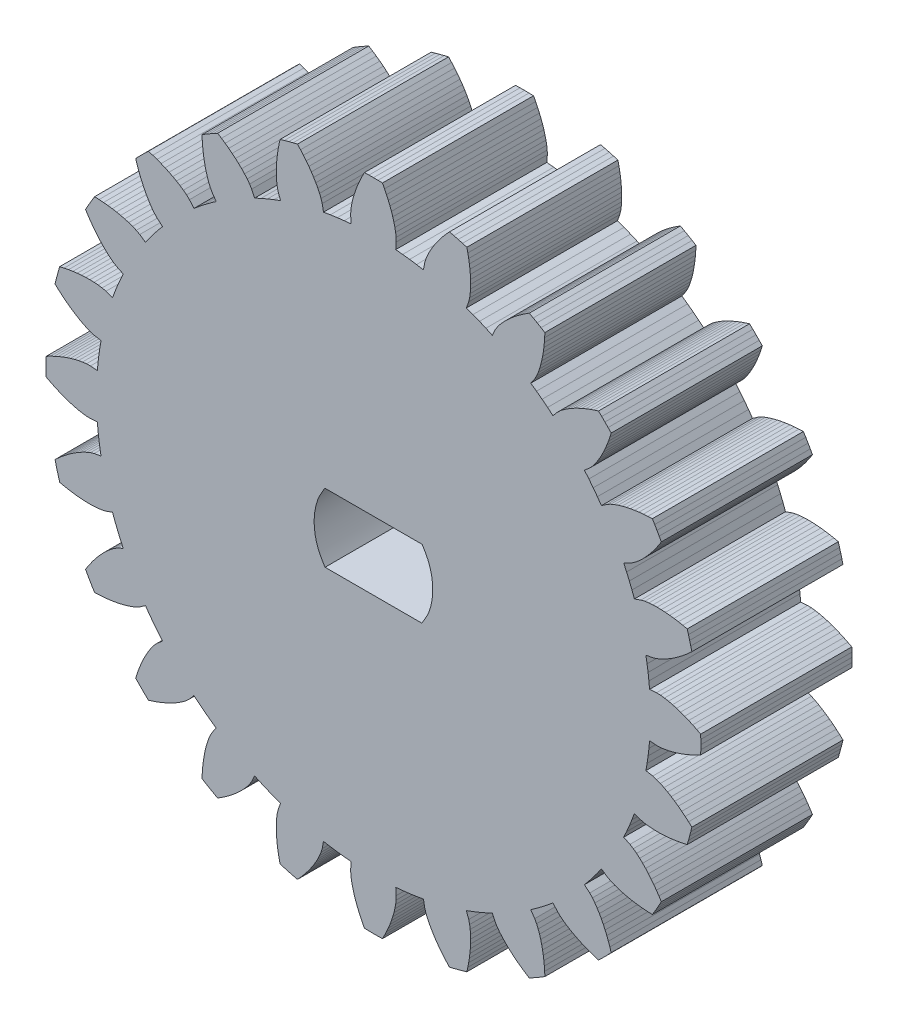
SolidWorks part; units mm, degrees
ref_plane "Front Plane" through (0, 0, 0) normal (0, 0, 1) x (1, 0, 0)
ref_plane "Top Plane" through (0, 0, 0) normal (0, 1, 0) x (1, 0, 0)
ref_plane "Right Plane" through (0, 0, 0) normal (1, 0, 0) x (0, 0, -1)
sketch "Model" plane through (0, 0, 0) normal (0, 0, 1) x (1, 0, 0)
  line L0 (117.0733, 147.6607) -> (117.2309, 147.6558)
  line L1 (117.2309, 147.6558) -> (117.3895, 147.636)
  line L2 (117.3895, 147.636) -> (117.5489, 147.6061)
  line L3 (117.5489, 147.6061) -> (117.7087, 147.5679)
  line L4 (117.7087, 147.5679) -> (117.8688, 147.5221)
  line L5 (117.8688, 147.5221) -> (118.029, 147.4694)
  line L6 (118.029, 147.4694) -> (118.1892, 147.4101)
  line L7 (118.1892, 147.4101) -> (118.3494, 147.3447)
  line L8 (118.3494, 147.3447) -> (118.5094, 147.2733)
  line L9 (118.5094, 147.2733) -> (118.6691, 147.1961)
  line L10 (118.6691, 147.1961) -> (118.8284, 147.1133)
  line L11 (118.8284, 147.1133) -> (118.8321, 146.9344)
  line L12 (118.8321, 146.9344) -> (118.8332, 146.7556)
  line L13 (118.8332, 146.7556) -> (118.8321, 146.5767)
  line L14 (118.8321, 146.5767) -> (118.8284, 146.3978)
  line L15 (118.8284, 146.3978) -> (118.6691, 146.315)
  line L16 (118.6691, 146.315) -> (118.5094, 146.2378)
  line L17 (118.5094, 146.2378) -> (118.3494, 146.1664)
  line L18 (118.3494, 146.1664) -> (118.1892, 146.101)
  line L19 (118.1892, 146.101) -> (118.029, 146.0418)
  line L20 (118.029, 146.0418) -> (117.8688, 145.989)
  line L21 (117.8688, 145.989) -> (117.7087, 145.9432)
  line L22 (117.7087, 145.9432) -> (117.5489, 145.905)
  line L23 (117.5489, 145.905) -> (117.3895, 145.8751)
  line L24 (117.3895, 145.8751) -> (117.2309, 145.8554)
  line L25 (117.2309, 145.8554) -> (117.0733, 145.8504)
  line L26 (117.0733, 145.8504) -> (116.7978, 145.8726)
  line L27 (116.7978, 145.8726) -> (116.772, 145.5958)
  line L28 (116.772, 145.5958) -> (116.7392, 145.3198)
  line L29 (116.7392, 145.3198) -> (116.6995, 145.0446)
  line L30 (116.6995, 145.0446) -> (116.6527, 144.7706)
  line L31 (116.6527, 144.7706) -> (116.9245, 144.7207)
  line L32 (116.9245, 144.7207) -> (117.0755, 144.6752)
  line L33 (117.0755, 144.6752) -> (117.2237, 144.615)
  line L34 (117.2237, 144.615) -> (117.3698, 144.5449)
  line L35 (117.3698, 144.5449) -> (117.5143, 144.4666)
  line L36 (117.5143, 144.4666) -> (117.657, 144.381)
  line L37 (117.657, 144.381) -> (117.7981, 144.2886)
  line L38 (117.7981, 144.2886) -> (117.9376, 144.1899)
  line L39 (117.9376, 144.1899) -> (118.0754, 144.0852)
  line L40 (118.0754, 144.0852) -> (118.2114, 143.9748)
  line L41 (118.2114, 143.9748) -> (118.3457, 143.8589)
  line L42 (118.3457, 143.8589) -> (118.4782, 143.7377)
  line L43 (118.4782, 143.7377) -> (118.4355, 143.564)
  line L44 (118.4355, 143.564) -> (118.3904, 143.3909)
  line L45 (118.3904, 143.3909) -> (118.3429, 143.2184)
  line L46 (118.3429, 143.2184) -> (118.293, 143.0466)
  line L47 (118.293, 143.0466) -> (118.1177, 143.0079)
  line L48 (118.1177, 143.0079) -> (117.9435, 142.9747)
  line L49 (117.9435, 142.9747) -> (117.7704, 142.9471)
  line L50 (117.7704, 142.9471) -> (117.5988, 142.9254)
  line L51 (117.5988, 142.9254) -> (117.4287, 142.9096)
  line L52 (117.4287, 142.9096) -> (117.2603, 142.9002)
  line L53 (117.2603, 142.9002) -> (117.0938, 142.8974)
  line L54 (117.0938, 142.8974) -> (116.9295, 142.9018)
  line L55 (116.9295, 142.9018) -> (116.7679, 142.9142)
  line L56 (116.7679, 142.9142) -> (116.6095, 142.9361)
  line L57 (116.6095, 142.9361) -> (116.456, 142.9722)
  line L58 (116.456, 142.9722) -> (116.1957, 143.0649)
  line L59 (116.1957, 143.0649) -> (116.0991, 142.8042)
  line L60 (116.0991, 142.8042) -> (115.996, 142.546)
  line L61 (115.996, 142.546) -> (115.8864, 142.2906)
  line L62 (115.8864, 142.2906) -> (115.7703, 142.038)
  line L63 (115.7703, 142.038) -> (116.0199, 141.9195)
  line L64 (116.0199, 141.9195) -> (116.154, 141.8364)
  line L65 (116.154, 141.8364) -> (116.2815, 141.7399)
  line L66 (116.2815, 141.7399) -> (116.4046, 141.6344)
  line L67 (116.4046, 141.6344) -> (116.5239, 141.5214)
  line L68 (116.5239, 141.5214) -> (116.6396, 141.4017)
  line L69 (116.6396, 141.4017) -> (116.7519, 141.2759)
  line L70 (116.7519, 141.2759) -> (116.8611, 141.1445)
  line L71 (116.8611, 141.1445) -> (116.9671, 141.0077)
  line L72 (116.9671, 141.0077) -> (117.07, 140.8659)
  line L73 (117.07, 140.8659) -> (117.1697, 140.7192)
  line L74 (117.1697, 140.7192) -> (117.2663, 140.5678)
  line L75 (117.2663, 140.5678) -> (117.18, 140.4111)
  line L76 (117.18, 140.4111) -> (117.0917, 140.2556)
  line L77 (117.0917, 140.2556) -> (117.0011, 140.1013)
  line L78 (117.0011, 140.1013) -> (116.9085, 139.9482)
  line L79 (116.9085, 139.9482) -> (116.7291, 139.9562)
  line L80 (116.7291, 139.9562) -> (116.5522, 139.9692)
  line L81 (116.5522, 139.9692) -> (116.378, 139.9874)
  line L82 (116.378, 139.9874) -> (116.2066, 140.0108)
  line L83 (116.2066, 140.0108) -> (116.0382, 140.0396)
  line L84 (116.0382, 140.0396) -> (115.8731, 140.074)
  line L85 (115.8731, 140.074) -> (115.7115, 140.1144)
  line L86 (115.7115, 140.1144) -> (115.554, 140.1612)
  line L87 (115.554, 140.1612) -> (115.4011, 140.215)
  line L88 (115.4011, 140.215) -> (115.2538, 140.2772)
  line L89 (115.2538, 140.2772) -> (115.1148, 140.3517)
  line L90 (115.1148, 140.3517) -> (114.8874, 140.5087)
  line L91 (114.8874, 140.5087) -> (114.7267, 140.2819)
  line L92 (114.7267, 140.2819) -> (114.5602, 140.0592)
  line L93 (114.5602, 140.0592) -> (114.3882, 139.8408)
  line L94 (114.3882, 139.8408) -> (114.2108, 139.6268)
  line L95 (114.2108, 139.6268) -> (114.4212, 139.4478)
  line L96 (114.4212, 139.4478) -> (114.5291, 139.3328)
  line L97 (114.5291, 139.3328) -> (114.6274, 139.2066)
  line L98 (114.6274, 139.2066) -> (114.719, 139.0728)
  line L99 (114.719, 139.0728) -> (114.8049, 138.9328)
  line L100 (114.8049, 138.9328) -> (114.8857, 138.7872)
  line L101 (114.8857, 138.7872) -> (114.9617, 138.6367)
  line L102 (114.9617, 138.6367) -> (115.0331, 138.4815)
  line L103 (115.0331, 138.4815) -> (115.1001, 138.3219)
  line L104 (115.1001, 138.3219) -> (115.1627, 138.1583)
  line L105 (115.1627, 138.1583) -> (115.2211, 137.9908)
  line L106 (115.2211, 137.9908) -> (115.2752, 137.8196)
  line L107 (115.2752, 137.8196) -> (115.1514, 137.6905)
  line L108 (115.1514, 137.6905) -> (115.0257, 137.5632)
  line L109 (115.0257, 137.5632) -> (114.8984, 137.4375)
  line L110 (114.8984, 137.4375) -> (114.7693, 137.3137)
  line L111 (114.7693, 137.3137) -> (114.5981, 137.3678)
  line L112 (114.5981, 137.3678) -> (114.4306, 137.4262)
  line L113 (114.4306, 137.4262) -> (114.267, 137.4888)
  line L114 (114.267, 137.4888) -> (114.1074, 137.5558)
  line L115 (114.1074, 137.5558) -> (113.9522, 137.6272)
  line L116 (113.9522, 137.6272) -> (113.8017, 137.7032)
  line L117 (113.8017, 137.7032) -> (113.6561, 137.784)
  line L118 (113.6561, 137.784) -> (113.516, 137.8699)
  line L119 (113.516, 137.8699) -> (113.3823, 137.9615)
  line L120 (113.3823, 137.9615) -> (113.2561, 138.0598)
  line L121 (113.2561, 138.0598) -> (113.1411, 138.1677)
  line L122 (113.1411, 138.1677) -> (112.9621, 138.3781)
  line L123 (112.9621, 138.3781) -> (112.7481, 138.2007)
  line L124 (112.7481, 138.2007) -> (112.5297, 138.0287)
  line L125 (112.5297, 138.0287) -> (112.307, 137.8622)
  line L126 (112.307, 137.8622) -> (112.0802, 137.7015)
  line L127 (112.0802, 137.7015) -> (112.2372, 137.4741)
  line L128 (112.2372, 137.4741) -> (112.3117, 137.3351)
  line L129 (112.3117, 137.3351) -> (112.3739, 137.1878)
  line L130 (112.3739, 137.1878) -> (112.4277, 137.0349)
  line L131 (112.4277, 137.0349) -> (112.4745, 136.8774)
  line L132 (112.4745, 136.8774) -> (112.5149, 136.7158)
  line L133 (112.5149, 136.7158) -> (112.5493, 136.5507)
  line L134 (112.5493, 136.5507) -> (112.5781, 136.3823)
  line L135 (112.5781, 136.3823) -> (112.6015, 136.2109)
  line L136 (112.6015, 136.2109) -> (112.6197, 136.0366)
  line L137 (112.6197, 136.0366) -> (112.6327, 135.8597)
  line L138 (112.6327, 135.8597) -> (112.6407, 135.6804)
  line L139 (112.6407, 135.6804) -> (112.4876, 135.5877)
  line L140 (112.4876, 135.5877) -> (112.3333, 135.4972)
  line L141 (112.3333, 135.4972) -> (112.1778, 135.4088)
  line L142 (112.1778, 135.4088) -> (112.0211, 135.3226)
  line L143 (112.0211, 135.3226) -> (111.8697, 135.4192)
  line L144 (111.8697, 135.4192) -> (111.723, 135.5189)
  line L145 (111.723, 135.5189) -> (111.5812, 135.6218)
  line L146 (111.5812, 135.6218) -> (111.4444, 135.7278)
  line L147 (111.4444, 135.7278) -> (111.313, 135.8369)
  line L148 (111.313, 135.8369) -> (111.1872, 135.9493)
  line L149 (111.1872, 135.9493) -> (111.0675, 136.065)
  line L150 (111.0675, 136.065) -> (110.9545, 136.1843)
  line L151 (110.9545, 136.1843) -> (110.849, 136.3074)
  line L152 (110.849, 136.3074) -> (110.7525, 136.4349)
  line L153 (110.7525, 136.4349) -> (110.6694, 136.5689)
  line L154 (110.6694, 136.5689) -> (110.5509, 136.8185)
  line L155 (110.5509, 136.8185) -> (110.2983, 136.7025)
  line L156 (110.2983, 136.7025) -> (110.0428, 136.5929)
  line L157 (110.0428, 136.5929) -> (109.7847, 136.4898)
  line L158 (109.7847, 136.4898) -> (109.524, 136.3932)
  line L159 (109.524, 136.3932) -> (109.6167, 136.1329)
  line L160 (109.6167, 136.1329) -> (109.6528, 135.9794)
  line L161 (109.6528, 135.9794) -> (109.6747, 135.821)
  line L162 (109.6747, 135.821) -> (109.6871, 135.6593)
  line L163 (109.6871, 135.6593) -> (109.6915, 135.4951)
  line L164 (109.6915, 135.4951) -> (109.6887, 135.3286)
  line L165 (109.6887, 135.3286) -> (109.6793, 135.1602)
  line L166 (109.6793, 135.1602) -> (109.6635, 134.9901)
  line L167 (109.6635, 134.9901) -> (109.6418, 134.8185)
  line L168 (109.6418, 134.8185) -> (109.6142, 134.6454)
  line L169 (109.6142, 134.6454) -> (109.581, 134.4712)
  line L170 (109.581, 134.4712) -> (109.5422, 134.2959)
  line L171 (109.5422, 134.2959) -> (109.3705, 134.246)
  line L172 (109.3705, 134.246) -> (109.198, 134.1985)
  line L173 (109.198, 134.1985) -> (109.0249, 134.1534)
  line L174 (109.0249, 134.1534) -> (108.8512, 134.1107)
  line L175 (108.8512, 134.1107) -> (108.7299, 134.2432)
  line L176 (108.7299, 134.2432) -> (108.6141, 134.3775)
  line L177 (108.6141, 134.3775) -> (108.5037, 134.5135)
  line L178 (108.5037, 134.5135) -> (108.399, 134.6513)
  line L179 (108.399, 134.6513) -> (108.3003, 134.7907)
  line L180 (108.3003, 134.7907) -> (108.2079, 134.9319)
  line L181 (108.2079, 134.9319) -> (108.1223, 135.0746)
  line L182 (108.1223, 135.0746) -> (108.044, 135.219)
  line L183 (108.044, 135.219) -> (107.9739, 135.3652)
  line L184 (107.9739, 135.3652) -> (107.9137, 135.5134)
  line L185 (107.9137, 135.5134) -> (107.8682, 135.6644)
  line L186 (107.8682, 135.6644) -> (107.8183, 135.9361)
  line L187 (107.8183, 135.9361) -> (107.5442, 135.8894)
  line L188 (107.5442, 135.8894) -> (107.2691, 135.8497)
  line L189 (107.2691, 135.8497) -> (106.9931, 135.8169)
  line L190 (106.9931, 135.8169) -> (106.7163, 135.7911)
  line L191 (106.7163, 135.7911) -> (106.7384, 135.5156)
  line L192 (106.7384, 135.5156) -> (106.7335, 135.358)
  line L193 (106.7335, 135.358) -> (106.7138, 135.1993)
  line L194 (106.7138, 135.1993) -> (106.6839, 135.04)
  line L195 (106.6839, 135.04) -> (106.6457, 134.8802)
  line L196 (106.6457, 134.8802) -> (106.5998, 134.7201)
  line L197 (106.5998, 134.7201) -> (106.5471, 134.5599)
  line L198 (106.5471, 134.5599) -> (106.4879, 134.3997)
  line L199 (106.4879, 134.3997) -> (106.4224, 134.2395)
  line L200 (106.4224, 134.2395) -> (106.351, 134.0795)
  line L201 (106.351, 134.0795) -> (106.2739, 133.9198)
  line L202 (106.2739, 133.9198) -> (106.1911, 133.7605)
  line L203 (106.1911, 133.7605) -> (106.0122, 133.7568)
  line L204 (106.0122, 133.7568) -> (105.8333, 133.7557)
  line L205 (105.8333, 133.7557) -> (105.6545, 133.7568)
  line L206 (105.6545, 133.7568) -> (105.4756, 133.7605)
  line L207 (105.4756, 133.7605) -> (105.3928, 133.9198)
  line L208 (105.3928, 133.9198) -> (105.3156, 134.0795)
  line L209 (105.3156, 134.0795) -> (105.2442, 134.2395)
  line L210 (105.2442, 134.2395) -> (105.1788, 134.3997)
  line L211 (105.1788, 134.3997) -> (105.1195, 134.5599)
  line L212 (105.1195, 134.5599) -> (105.0668, 134.7201)
  line L213 (105.0668, 134.7201) -> (105.021, 134.8802)
  line L214 (105.021, 134.8802) -> (104.9827, 135.04)
  line L215 (104.9827, 135.04) -> (104.9529, 135.1993)
  line L216 (104.9529, 135.1993) -> (104.9331, 135.358)
  line L217 (104.9331, 135.358) -> (104.9282, 135.5156)
  line L218 (104.9282, 135.5156) -> (104.9504, 135.7911)
  line L219 (104.9504, 135.7911) -> (104.6736, 135.8169)
  line L220 (104.6736, 135.8169) -> (104.3976, 135.8497)
  line L221 (104.3976, 135.8497) -> (104.1224, 135.8894)
  line L222 (104.1224, 135.8894) -> (103.8484, 135.9361)
  line L223 (103.8484, 135.9361) -> (103.7985, 135.6644)
  line L224 (103.7985, 135.6644) -> (103.753, 135.5134)
  line L225 (103.753, 135.5134) -> (103.6928, 135.3652)
  line L226 (103.6928, 135.3652) -> (103.6227, 135.219)
  line L227 (103.6227, 135.219) -> (103.5444, 135.0746)
  line L228 (103.5444, 135.0746) -> (103.4587, 134.9319)
  line L229 (103.4587, 134.9319) -> (103.3663, 134.7907)
  line L230 (103.3663, 134.7907) -> (103.2677, 134.6513)
  line L231 (103.2677, 134.6513) -> (103.163, 134.5135)
  line L232 (103.163, 134.5135) -> (103.0526, 134.3775)
  line L233 (103.0526, 134.3775) -> (102.9367, 134.2432)
  line L234 (102.9367, 134.2432) -> (102.8155, 134.1107)
  line L235 (102.8155, 134.1107) -> (102.6418, 134.1534)
  line L236 (102.6418, 134.1534) -> (102.4687, 134.1985)
  line L237 (102.4687, 134.1985) -> (102.2962, 134.246)
  line L238 (102.2962, 134.246) -> (102.1244, 134.2959)
  line L239 (102.1244, 134.2959) -> (102.0857, 134.4712)
  line L240 (102.0857, 134.4712) -> (102.0525, 134.6454)
  line L241 (102.0525, 134.6454) -> (102.0249, 134.8185)
  line L242 (102.0249, 134.8185) -> (102.0032, 134.9901)
  line L243 (102.0032, 134.9901) -> (101.9874, 135.1602)
  line L244 (101.9874, 135.1602) -> (101.978, 135.3286)
  line L245 (101.978, 135.3286) -> (101.9751, 135.4951)
  line L246 (101.9751, 135.4951) -> (101.9795, 135.6593)
  line L247 (101.9795, 135.6593) -> (101.992, 135.821)
  line L248 (101.992, 135.821) -> (102.0139, 135.9794)
  line L249 (102.0139, 135.9794) -> (102.0499, 136.1329)
  line L250 (102.0499, 136.1329) -> (102.1427, 136.3932)
  line L251 (102.1427, 136.3932) -> (101.882, 136.4898)
  line L252 (101.882, 136.4898) -> (101.6238, 136.5929)
  line L253 (101.6238, 136.5929) -> (101.3684, 136.7025)
  line L254 (101.3684, 136.7025) -> (101.1157, 136.8185)
  line L255 (101.1157, 136.8185) -> (100.9972, 136.5689)
  line L256 (100.9972, 136.5689) -> (100.9142, 136.4349)
  line L257 (100.9142, 136.4349) -> (100.8177, 136.3074)
  line L258 (100.8177, 136.3074) -> (100.7122, 136.1843)
  line L259 (100.7122, 136.1843) -> (100.5991, 136.065)
  line L260 (100.5991, 136.065) -> (100.4794, 135.9493)
  line L261 (100.4794, 135.9493) -> (100.3537, 135.8369)
  line L262 (100.3537, 135.8369) -> (100.2222, 135.7278)
  line L263 (100.2222, 135.7278) -> (100.0855, 135.6218)
  line L264 (100.0855, 135.6218) -> (99.9437, 135.5189)
  line L265 (99.9437, 135.5189) -> (99.797, 135.4192)
  line L266 (99.797, 135.4192) -> (99.6456, 135.3226)
  line L267 (99.6456, 135.3226) -> (99.4889, 135.4088)
  line L268 (99.4889, 135.4088) -> (99.3333, 135.4972)
  line L269 (99.3333, 135.4972) -> (99.179, 135.5877)
  line L270 (99.179, 135.5877) -> (99.026, 135.6804)
  line L271 (99.026, 135.6804) -> (99.034, 135.8597)
  line L272 (99.034, 135.8597) -> (99.047, 136.0366)
  line L273 (99.047, 136.0366) -> (99.0651, 136.2109)
  line L274 (99.0651, 136.2109) -> (99.0885, 136.3823)
  line L275 (99.0885, 136.3823) -> (99.1173, 136.5507)
  line L276 (99.1173, 136.5507) -> (99.1518, 136.7158)
  line L277 (99.1518, 136.7158) -> (99.1922, 136.8774)
  line L278 (99.1922, 136.8774) -> (99.2389, 137.0349)
  line L279 (99.2389, 137.0349) -> (99.2927, 137.1878)
  line L280 (99.2927, 137.1878) -> (99.355, 137.3351)
  line L281 (99.355, 137.3351) -> (99.4295, 137.4741)
  line L282 (99.4295, 137.4741) -> (99.5864, 137.7015)
  line L283 (99.5864, 137.7015) -> (99.3596, 137.8622)
  line L284 (99.3596, 137.8622) -> (99.137, 138.0287)
  line L285 (99.137, 138.0287) -> (98.9186, 138.2007)
  line L286 (98.9186, 138.2007) -> (98.7046, 138.3781)
  line L287 (98.7046, 138.3781) -> (98.5255, 138.1677)
  line L288 (98.5255, 138.1677) -> (98.4106, 138.0598)
  line L289 (98.4106, 138.0598) -> (98.2844, 137.9615)
  line L290 (98.2844, 137.9615) -> (98.1506, 137.8699)
  line L291 (98.1506, 137.8699) -> (98.0106, 137.784)
  line L292 (98.0106, 137.784) -> (97.865, 137.7032)
  line L293 (97.865, 137.7032) -> (97.7144, 137.6272)
  line L294 (97.7144, 137.6272) -> (97.5593, 137.5558)
  line L295 (97.5593, 137.5558) -> (97.3997, 137.4888)
  line L296 (97.3997, 137.4888) -> (97.2361, 137.4262)
  line L297 (97.2361, 137.4262) -> (97.0686, 137.3678)
  line L298 (97.0686, 137.3678) -> (96.8974, 137.3137)
  line L299 (96.8974, 137.3137) -> (96.7683, 137.4375)
  line L300 (96.7683, 137.4375) -> (96.6409, 137.5632)
  line L301 (96.6409, 137.5632) -> (96.5153, 137.6905)
  line L302 (96.5153, 137.6905) -> (96.3915, 137.8196)
  line L303 (96.3915, 137.8196) -> (96.4456, 137.9908)
  line L304 (96.4456, 137.9908) -> (96.504, 138.1583)
  line L305 (96.504, 138.1583) -> (96.5666, 138.3219)
  line L306 (96.5666, 138.3219) -> (96.6336, 138.4815)
  line L307 (96.6336, 138.4815) -> (96.705, 138.6367)
  line L308 (96.705, 138.6367) -> (96.781, 138.7872)
  line L309 (96.781, 138.7872) -> (96.8618, 138.9328)
  line L310 (96.8618, 138.9328) -> (96.9477, 139.0728)
  line L311 (96.9477, 139.0728) -> (97.0393, 139.2066)
  line L312 (97.0393, 139.2066) -> (97.1375, 139.3328)
  line L313 (97.1375, 139.3328) -> (97.2455, 139.4478)
  line L314 (97.2455, 139.4478) -> (97.4559, 139.6268)
  line L315 (97.4559, 139.6268) -> (97.2784, 139.8408)
  line L316 (97.2784, 139.8408) -> (97.1065, 140.0592)
  line L317 (97.1065, 140.0592) -> (96.94, 140.2819)
  line L318 (96.94, 140.2819) -> (96.7793, 140.5087)
  line L319 (96.7793, 140.5087) -> (96.5518, 140.3517)
  line L320 (96.5518, 140.3517) -> (96.4129, 140.2772)
  line L321 (96.4129, 140.2772) -> (96.2656, 140.215)
  line L322 (96.2656, 140.215) -> (96.1126, 140.1612)
  line L323 (96.1126, 140.1612) -> (95.9551, 140.1144)
  line L324 (95.9551, 140.1144) -> (95.7936, 140.074)
  line L325 (95.7936, 140.074) -> (95.6285, 140.0396)
  line L326 (95.6285, 140.0396) -> (95.4601, 140.0108)
  line L327 (95.4601, 140.0108) -> (95.2887, 139.9874)
  line L328 (95.2887, 139.9874) -> (95.1144, 139.9692)
  line L329 (95.1144, 139.9692) -> (94.9375, 139.9562)
  line L330 (94.9375, 139.9562) -> (94.7581, 139.9482)
  line L331 (94.7581, 139.9482) -> (94.6655, 140.1013)
  line L332 (94.6655, 140.1013) -> (94.575, 140.2556)
  line L333 (94.575, 140.2556) -> (94.4866, 140.4111)
  line L334 (94.4866, 140.4111) -> (94.4004, 140.5678)
  line L335 (94.4004, 140.5678) -> (94.497, 140.7192)
  line L336 (94.497, 140.7192) -> (94.5967, 140.8659)
  line L337 (94.5967, 140.8659) -> (94.6996, 141.0077)
  line L338 (94.6996, 141.0077) -> (94.8056, 141.1445)
  line L339 (94.8056, 141.1445) -> (94.9147, 141.2759)
  line L340 (94.9147, 141.2759) -> (95.0271, 141.4017)
  line L341 (95.0271, 141.4017) -> (95.1428, 141.5214)
  line L342 (95.1428, 141.5214) -> (95.2621, 141.6344)
  line L343 (95.2621, 141.6344) -> (95.3851, 141.7399)
  line L344 (95.3851, 141.7399) -> (95.5127, 141.8364)
  line L345 (95.5127, 141.8364) -> (95.6467, 141.9195)
  line L346 (95.6467, 141.9195) -> (95.8963, 142.038)
  line L347 (95.8963, 142.038) -> (95.7803, 142.2906)
  line L348 (95.7803, 142.2906) -> (95.6707, 142.546)
  line L349 (95.6707, 142.546) -> (95.5675, 142.8042)
  line L350 (95.5675, 142.8042) -> (95.471, 143.0649)
  line L351 (95.471, 143.0649) -> (95.2107, 142.9722)
  line L352 (95.2107, 142.9722) -> (95.0572, 142.9361)
  line L353 (95.0572, 142.9361) -> (94.8987, 142.9142)
  line L354 (94.8987, 142.9142) -> (94.7371, 142.9018)
  line L355 (94.7371, 142.9018) -> (94.5729, 142.8974)
  line L356 (94.5729, 142.8974) -> (94.4064, 142.9002)
  line L357 (94.4064, 142.9002) -> (94.238, 142.9096)
  line L358 (94.238, 142.9096) -> (94.0679, 142.9254)
  line L359 (94.0679, 142.9254) -> (93.8962, 142.9471)
  line L360 (93.8962, 142.9471) -> (93.7232, 142.9747)
  line L361 (93.7232, 142.9747) -> (93.549, 143.0079)
  line L362 (93.549, 143.0079) -> (93.3736, 143.0466)
  line L363 (93.3736, 143.0466) -> (93.3238, 143.2184)
  line L364 (93.3238, 143.2184) -> (93.2763, 143.3909)
  line L365 (93.2763, 143.3909) -> (93.2312, 143.564)
  line L366 (93.2312, 143.564) -> (93.1885, 143.7377)
  line L367 (93.1885, 143.7377) -> (93.321, 143.8589)
  line L368 (93.321, 143.8589) -> (93.4552, 143.9748)
  line L369 (93.4552, 143.9748) -> (93.5913, 144.0852)
  line L370 (93.5913, 144.0852) -> (93.729, 144.1899)
  line L371 (93.729, 144.1899) -> (93.8685, 144.2886)
  line L372 (93.8685, 144.2886) -> (94.0096, 144.381)
  line L373 (94.0096, 144.381) -> (94.1524, 144.4666)
  line L374 (94.1524, 144.4666) -> (94.2968, 144.5449)
  line L375 (94.2968, 144.5449) -> (94.443, 144.615)
  line L376 (94.443, 144.615) -> (94.5912, 144.6752)
  line L377 (94.5912, 144.6752) -> (94.7421, 144.7207)
  line L378 (94.7421, 144.7207) -> (95.0139, 144.7706)
  line L379 (95.0139, 144.7706) -> (94.9672, 145.0446)
  line L380 (94.9672, 145.0446) -> (94.9274, 145.3198)
  line L381 (94.9274, 145.3198) -> (94.8947, 145.5958)
  line L382 (94.8947, 145.5958) -> (94.8688, 145.8726)
  line L383 (94.8688, 145.8726) -> (94.5934, 145.8504)
  line L384 (94.5934, 145.8504) -> (94.4358, 145.8554)
  line L385 (94.4358, 145.8554) -> (94.2771, 145.8751)
  line L386 (94.2771, 145.8751) -> (94.1178, 145.905)
  line L387 (94.1178, 145.905) -> (93.958, 145.9432)
  line L388 (93.958, 145.9432) -> (93.7979, 145.989)
  line L389 (93.7979, 145.989) -> (93.6377, 146.0418)
  line L390 (93.6377, 146.0418) -> (93.4774, 146.101)
  line L391 (93.4774, 146.101) -> (93.3173, 146.1664)
  line L392 (93.3173, 146.1664) -> (93.1573, 146.2378)
  line L393 (93.1573, 146.2378) -> (92.9976, 146.315)
  line L394 (92.9976, 146.315) -> (92.8383, 146.3978)
  line L395 (92.8383, 146.3978) -> (92.8346, 146.5767)
  line L396 (92.8346, 146.5767) -> (92.8334, 146.7556)
  line L397 (92.8334, 146.7556) -> (92.8346, 146.9344)
  line L398 (92.8346, 146.9344) -> (92.8383, 147.1133)
  line L399 (92.8383, 147.1133) -> (92.9976, 147.1961)
  line L400 (92.9976, 147.1961) -> (93.1573, 147.2733)
  line L401 (93.1573, 147.2733) -> (93.3173, 147.3447)
  line L402 (93.3173, 147.3447) -> (93.4774, 147.4101)
  line L403 (93.4774, 147.4101) -> (93.6377, 147.4694)
  line L404 (93.6377, 147.4694) -> (93.7979, 147.5221)
  line L405 (93.7979, 147.5221) -> (93.958, 147.5679)
  line L406 (93.958, 147.5679) -> (94.1178, 147.6061)
  line L407 (94.1178, 147.6061) -> (94.2771, 147.636)
  line L408 (94.2771, 147.636) -> (94.4358, 147.6558)
  line L409 (94.4358, 147.6558) -> (94.5934, 147.6607)
  line L410 (94.5934, 147.6607) -> (94.8688, 147.6385)
  line L411 (94.8688, 147.6385) -> (94.8947, 147.9153)
  line L412 (94.8947, 147.9153) -> (94.9274, 148.1913)
  line L413 (94.9274, 148.1913) -> (94.9672, 148.4665)
  line L414 (94.9672, 148.4665) -> (95.0139, 148.7405)
  line L415 (95.0139, 148.7405) -> (94.7421, 148.7904)
  line L416 (94.7421, 148.7904) -> (94.5912, 148.8359)
  line L417 (94.5912, 148.8359) -> (94.443, 148.8961)
  line L418 (94.443, 148.8961) -> (94.2968, 148.9662)
  line L419 (94.2968, 148.9662) -> (94.1524, 149.0445)
  line L420 (94.1524, 149.0445) -> (94.0096, 149.1301)
  line L421 (94.0096, 149.1301) -> (93.8685, 149.2225)
  line L422 (93.8685, 149.2225) -> (93.729, 149.3212)
  line L423 (93.729, 149.3212) -> (93.5913, 149.4259)
  line L424 (93.5913, 149.4259) -> (93.4552, 149.5363)
  line L425 (93.4552, 149.5363) -> (93.321, 149.6522)
  line L426 (93.321, 149.6522) -> (93.1885, 149.7734)
  line L427 (93.1885, 149.7734) -> (93.2312, 149.9471)
  line L428 (93.2312, 149.9471) -> (93.2763, 150.1202)
  line L429 (93.2763, 150.1202) -> (93.3238, 150.2927)
  line L430 (93.3238, 150.2927) -> (93.3736, 150.4645)
  line L431 (93.3736, 150.4645) -> (93.549, 150.5032)
  line L432 (93.549, 150.5032) -> (93.7232, 150.5364)
  line L433 (93.7232, 150.5364) -> (93.8962, 150.564)
  line L434 (93.8962, 150.564) -> (94.0679, 150.5857)
  line L435 (94.0679, 150.5857) -> (94.238, 150.6015)
  line L436 (94.238, 150.6015) -> (94.4064, 150.6109)
  line L437 (94.4064, 150.6109) -> (94.5729, 150.6138)
  line L438 (94.5729, 150.6138) -> (94.7371, 150.6094)
  line L439 (94.7371, 150.6094) -> (94.8987, 150.5969)
  line L440 (94.8987, 150.5969) -> (95.0572, 150.575)
  line L441 (95.0572, 150.575) -> (95.2107, 150.5389)
  line L442 (95.2107, 150.5389) -> (95.471, 150.4462)
  line L443 (95.471, 150.4462) -> (95.5675, 150.7069)
  line L444 (95.5675, 150.7069) -> (95.6707, 150.9651)
  line L445 (95.6707, 150.9651) -> (95.7803, 151.2205)
  line L446 (95.7803, 151.2205) -> (95.8963, 151.4732)
  line L447 (95.8963, 151.4732) -> (95.6467, 151.5917)
  line L448 (95.6467, 151.5917) -> (95.5127, 151.6747)
  line L449 (95.5127, 151.6747) -> (95.3851, 151.7712)
  line L450 (95.3851, 151.7712) -> (95.2621, 151.8767)
  line L451 (95.2621, 151.8767) -> (95.1428, 151.9898)
  line L452 (95.1428, 151.9898) -> (95.0271, 152.1095)
  line L453 (95.0271, 152.1095) -> (94.9147, 152.2352)
  line L454 (94.9147, 152.2352) -> (94.8056, 152.3666)
  line L455 (94.8056, 152.3666) -> (94.6996, 152.5034)
  line L456 (94.6996, 152.5034) -> (94.5967, 152.6452)
  line L457 (94.5967, 152.6452) -> (94.497, 152.7919)
  line L458 (94.497, 152.7919) -> (94.4004, 152.9433)
  line L459 (94.4004, 152.9433) -> (94.4866, 153.1)
  line L460 (94.4866, 153.1) -> (94.575, 153.2556)
  line L461 (94.575, 153.2556) -> (94.6655, 153.4098)
  line L462 (94.6655, 153.4098) -> (94.7581, 153.5629)
  line L463 (94.7581, 153.5629) -> (94.9375, 153.5549)
  line L464 (94.9375, 153.5549) -> (95.1144, 153.5419)
  line L465 (95.1144, 153.5419) -> (95.2887, 153.5238)
  line L466 (95.2887, 153.5238) -> (95.4601, 153.5004)
  line L467 (95.4601, 153.5004) -> (95.6285, 153.4715)
  line L468 (95.6285, 153.4715) -> (95.7936, 153.4371)
  line L469 (95.7936, 153.4371) -> (95.9551, 153.3967)
  line L470 (95.9551, 153.3967) -> (96.1126, 153.35)
  line L471 (96.1126, 153.35) -> (96.2656, 153.2961)
  line L472 (96.2656, 153.2961) -> (96.4129, 153.2339)
  line L473 (96.4129, 153.2339) -> (96.5518, 153.1594)
  line L474 (96.5518, 153.1594) -> (96.7793, 153.0025)
  line L475 (96.7793, 153.0025) -> (96.94, 153.2293)
  line L476 (96.94, 153.2293) -> (97.1065, 153.4519)
  line L477 (97.1065, 153.4519) -> (97.2784, 153.6703)
  line L478 (97.2784, 153.6703) -> (97.4559, 153.8843)
  line L479 (97.4559, 153.8843) -> (97.2455, 154.0634)
  line L480 (97.2455, 154.0634) -> (97.1375, 154.1783)
  line L481 (97.1375, 154.1783) -> (97.0393, 154.3045)
  line L482 (97.0393, 154.3045) -> (96.9477, 154.4383)
  line L483 (96.9477, 154.4383) -> (96.8618, 154.5783)
  line L484 (96.8618, 154.5783) -> (96.781, 154.7239)
  line L485 (96.781, 154.7239) -> (96.705, 154.8744)
  line L486 (96.705, 154.8744) -> (96.6336, 155.0296)
  line L487 (96.6336, 155.0296) -> (96.5666, 155.1892)
  line L488 (96.5666, 155.1892) -> (96.504, 155.3528)
  line L489 (96.504, 155.3528) -> (96.4456, 155.5203)
  line L490 (96.4456, 155.5203) -> (96.3915, 155.6915)
  line L491 (96.3915, 155.6915) -> (96.5153, 155.8206)
  line L492 (96.5153, 155.8206) -> (96.6409, 155.948)
  line L493 (96.6409, 155.948) -> (96.7683, 156.0736)
  line L494 (96.7683, 156.0736) -> (96.8974, 156.1974)
  line L495 (96.8974, 156.1974) -> (97.0686, 156.1433)
  line L496 (97.0686, 156.1433) -> (97.2361, 156.0849)
  line L497 (97.2361, 156.0849) -> (97.3997, 156.0223)
  line L498 (97.3997, 156.0223) -> (97.5593, 155.9553)
  line L499 (97.5593, 155.9553) -> (97.7144, 155.8839)
  line L500 (97.7144, 155.8839) -> (97.865, 155.8079)
  line L501 (97.865, 155.8079) -> (98.0106, 155.7271)
  line L502 (98.0106, 155.7271) -> (98.1506, 155.6412)
  line L503 (98.1506, 155.6412) -> (98.2844, 155.5496)
  line L504 (98.2844, 155.5496) -> (98.4106, 155.4514)
  line L505 (98.4106, 155.4514) -> (98.5255, 155.3434)
  line L506 (98.5255, 155.3434) -> (98.7046, 155.133)
  line L507 (98.7046, 155.133) -> (98.9186, 155.3104)
  line L508 (98.9186, 155.3104) -> (99.137, 155.4824)
  line L509 (99.137, 155.4824) -> (99.3596, 155.6489)
  line L510 (99.3596, 155.6489) -> (99.5864, 155.8096)
  line L511 (99.5864, 155.8096) -> (99.4295, 156.0371)
  line L512 (99.4295, 156.0371) -> (99.355, 156.176)
  line L513 (99.355, 156.176) -> (99.2927, 156.3233)
  line L514 (99.2927, 156.3233) -> (99.2389, 156.4762)
  line L515 (99.2389, 156.4762) -> (99.1922, 156.6338)
  line L516 (99.1922, 156.6338) -> (99.1518, 156.7953)
  line L517 (99.1518, 156.7953) -> (99.1173, 156.9604)
  line L518 (99.1173, 156.9604) -> (99.0885, 157.1288)
  line L519 (99.0885, 157.1288) -> (99.0651, 157.3002)
  line L520 (99.0651, 157.3002) -> (99.047, 157.4745)
  line L521 (99.047, 157.4745) -> (99.034, 157.6514)
  line L522 (99.034, 157.6514) -> (99.026, 157.8307)
  line L523 (99.026, 157.8307) -> (99.179, 157.9234)
  line L524 (99.179, 157.9234) -> (99.3333, 158.0139)
  line L525 (99.3333, 158.0139) -> (99.4889, 158.1023)
  line L526 (99.4889, 158.1023) -> (99.6456, 158.1885)
  line L527 (99.6456, 158.1885) -> (99.797, 158.0919)
  line L528 (99.797, 158.0919) -> (99.9437, 157.9922)
  line L529 (99.9437, 157.9922) -> (100.0855, 157.8893)
  line L530 (100.0855, 157.8893) -> (100.2222, 157.7833)
  line L531 (100.2222, 157.7833) -> (100.3537, 157.6742)
  line L532 (100.3537, 157.6742) -> (100.4794, 157.5618)
  line L533 (100.4794, 157.5618) -> (100.5991, 157.4461)
  line L534 (100.5991, 157.4461) -> (100.7122, 157.3268)
  line L535 (100.7122, 157.3268) -> (100.8177, 157.2038)
  line L536 (100.8177, 157.2038) -> (100.9142, 157.0762)
  line L537 (100.9142, 157.0762) -> (100.9972, 156.9422)
  line L538 (100.9972, 156.9422) -> (101.1157, 156.6926)
  line L539 (101.1157, 156.6926) -> (101.3684, 156.8086)
  line L540 (101.3684, 156.8086) -> (101.6238, 156.9182)
  line L541 (101.6238, 156.9182) -> (101.882, 157.0214)
  line L542 (101.882, 157.0214) -> (102.1427, 157.1179)
  line L543 (102.1427, 157.1179) -> (102.0499, 157.3782)
  line L544 (102.0499, 157.3782) -> (102.0139, 157.5317)
  line L545 (102.0139, 157.5317) -> (101.992, 157.6901)
  line L546 (101.992, 157.6901) -> (101.9795, 157.8518)
  line L547 (101.9795, 157.8518) -> (101.9751, 158.016)
  line L548 (101.9751, 158.016) -> (101.978, 158.1825)
  line L549 (101.978, 158.1825) -> (101.9874, 158.3509)
  line L550 (101.9874, 158.3509) -> (102.0032, 158.521)
  line L551 (102.0032, 158.521) -> (102.0249, 158.6927)
  line L552 (102.0249, 158.6927) -> (102.0525, 158.8657)
  line L553 (102.0525, 158.8657) -> (102.0857, 159.0399)
  line L554 (102.0857, 159.0399) -> (102.1244, 159.2152)
  line L555 (102.1244, 159.2152) -> (102.2962, 159.2651)
  line L556 (102.2962, 159.2651) -> (102.4687, 159.3126)
  line L557 (102.4687, 159.3126) -> (102.6418, 159.3577)
  line L558 (102.6418, 159.3577) -> (102.8155, 159.4004)
  line L559 (102.8155, 159.4004) -> (102.9367, 159.2679)
  line L560 (102.9367, 159.2679) -> (103.0526, 159.1337)
  line L561 (103.0526, 159.1337) -> (103.163, 158.9976)
  line L562 (103.163, 158.9976) -> (103.2677, 158.8598)
  line L563 (103.2677, 158.8598) -> (103.3663, 158.7204)
  line L564 (103.3663, 158.7204) -> (103.4587, 158.5793)
  line L565 (103.4587, 158.5793) -> (103.5444, 158.4365)
  line L566 (103.5444, 158.4365) -> (103.6227, 158.2921)
  line L567 (103.6227, 158.2921) -> (103.6928, 158.1459)
  line L568 (103.6928, 158.1459) -> (103.753, 157.9977)
  line L569 (103.753, 157.9977) -> (103.7985, 157.8467)
  line L570 (103.7985, 157.8467) -> (103.8484, 157.575)
  line L571 (103.8484, 157.575) -> (104.1224, 157.6217)
  line L572 (104.1224, 157.6217) -> (104.3976, 157.6614)
  line L573 (104.3976, 157.6614) -> (104.6736, 157.6942)
  line L574 (104.6736, 157.6942) -> (104.9504, 157.7201)
  line L575 (104.9504, 157.7201) -> (104.9282, 157.9955)
  line L576 (104.9282, 157.9955) -> (104.9331, 158.1531)
  line L577 (104.9331, 158.1531) -> (104.9529, 158.3118)
  line L578 (104.9529, 158.3118) -> (104.9827, 158.4711)
  line L579 (104.9827, 158.4711) -> (105.021, 158.6309)
  line L580 (105.021, 158.6309) -> (105.0668, 158.791)
  line L581 (105.0668, 158.791) -> (105.1195, 158.9512)
  line L582 (105.1195, 158.9512) -> (105.1788, 159.1114)
  line L583 (105.1788, 159.1114) -> (105.2442, 159.2716)
  line L584 (105.2442, 159.2716) -> (105.3156, 159.4316)
  line L585 (105.3156, 159.4316) -> (105.3928, 159.5913)
  line L586 (105.3928, 159.5913) -> (105.4756, 159.7506)
  line L587 (105.4756, 159.7506) -> (105.6545, 159.7543)
  line L588 (105.6545, 159.7543) -> (105.8333, 159.7554)
  line L589 (105.8333, 159.7554) -> (106.0122, 159.7543)
  line L590 (106.0122, 159.7543) -> (106.1911, 159.7506)
  line L591 (106.1911, 159.7506) -> (106.2739, 159.5913)
  line L592 (106.2739, 159.5913) -> (106.351, 159.4316)
  line L593 (106.351, 159.4316) -> (106.4224, 159.2716)
  line L594 (106.4224, 159.2716) -> (106.4879, 159.1114)
  line L595 (106.4879, 159.1114) -> (106.5471, 158.9512)
  line L596 (106.5471, 158.9512) -> (106.5998, 158.791)
  line L597 (106.5998, 158.791) -> (106.6457, 158.6309)
  line L598 (106.6457, 158.6309) -> (106.6839, 158.4711)
  line L599 (106.6839, 158.4711) -> (106.7138, 158.3118)
  line L600 (106.7138, 158.3118) -> (106.7335, 158.1531)
  line L601 (106.7335, 158.1531) -> (106.7384, 157.9955)
  line L602 (106.7384, 157.9955) -> (106.7163, 157.7201)
  line L603 (106.7163, 157.7201) -> (106.9931, 157.6942)
  line L604 (106.9931, 157.6942) -> (107.2691, 157.6614)
  line L605 (107.2691, 157.6614) -> (107.5442, 157.6217)
  line L606 (107.5442, 157.6217) -> (107.8183, 157.575)
  line L607 (107.8183, 157.575) -> (107.8682, 157.8467)
  line L608 (107.8682, 157.8467) -> (107.9137, 157.9977)
  line L609 (107.9137, 157.9977) -> (107.9739, 158.1459)
  line L610 (107.9739, 158.1459) -> (108.044, 158.2921)
  line L611 (108.044, 158.2921) -> (108.1223, 158.4365)
  line L612 (108.1223, 158.4365) -> (108.2079, 158.5793)
  line L613 (108.2079, 158.5793) -> (108.3003, 158.7204)
  line L614 (108.3003, 158.7204) -> (108.399, 158.8598)
  line L615 (108.399, 158.8598) -> (108.5037, 158.9976)
  line L616 (108.5037, 158.9976) -> (108.6141, 159.1337)
  line L617 (108.6141, 159.1337) -> (108.7299, 159.2679)
  line L618 (108.7299, 159.2679) -> (108.8512, 159.4004)
  line L619 (108.8512, 159.4004) -> (109.0249, 159.3577)
  line L620 (109.0249, 159.3577) -> (109.198, 159.3126)
  line L621 (109.198, 159.3126) -> (109.3705, 159.2651)
  line L622 (109.3705, 159.2651) -> (109.5422, 159.2152)
  line L623 (109.5422, 159.2152) -> (109.581, 159.0399)
  line L624 (109.581, 159.0399) -> (109.6142, 158.8657)
  line L625 (109.6142, 158.8657) -> (109.6418, 158.6927)
  line L626 (109.6418, 158.6927) -> (109.6635, 158.521)
  line L627 (109.6635, 158.521) -> (109.6793, 158.3509)
  line L628 (109.6793, 158.3509) -> (109.6887, 158.1825)
  line L629 (109.6887, 158.1825) -> (109.6915, 158.016)
  line L630 (109.6915, 158.016) -> (109.6871, 157.8518)
  line L631 (109.6871, 157.8518) -> (109.6747, 157.6901)
  line L632 (109.6747, 157.6901) -> (109.6528, 157.5317)
  line L633 (109.6528, 157.5317) -> (109.6167, 157.3782)
  line L634 (109.6167, 157.3782) -> (109.524, 157.1179)
  line L635 (109.524, 157.1179) -> (109.7847, 157.0214)
  line L636 (109.7847, 157.0214) -> (110.0428, 156.9182)
  line L637 (110.0428, 156.9182) -> (110.2983, 156.8086)
  line L638 (110.2983, 156.8086) -> (110.5509, 156.6926)
  line L639 (110.5509, 156.6926) -> (110.6694, 156.9422)
  line L640 (110.6694, 156.9422) -> (110.7525, 157.0762)
  line L641 (110.7525, 157.0762) -> (110.849, 157.2038)
  line L642 (110.849, 157.2038) -> (110.9545, 157.3268)
  line L643 (110.9545, 157.3268) -> (111.0675, 157.4461)
  line L644 (111.0675, 157.4461) -> (111.1872, 157.5618)
  line L645 (111.1872, 157.5618) -> (111.313, 157.6742)
  line L646 (111.313, 157.6742) -> (111.4444, 157.7833)
  line L647 (111.4444, 157.7833) -> (111.5812, 157.8893)
  line L648 (111.5812, 157.8893) -> (111.723, 157.9922)
  line L649 (111.723, 157.9922) -> (111.8697, 158.0919)
  line L650 (111.8697, 158.0919) -> (112.0211, 158.1885)
  line L651 (112.0211, 158.1885) -> (112.1778, 158.1023)
  line L652 (112.1778, 158.1023) -> (112.3333, 158.0139)
  line L653 (112.3333, 158.0139) -> (112.4876, 157.9234)
  line L654 (112.4876, 157.9234) -> (112.6407, 157.8307)
  line L655 (112.6407, 157.8307) -> (112.6327, 157.6514)
  line L656 (112.6327, 157.6514) -> (112.6197, 157.4745)
  line L657 (112.6197, 157.4745) -> (112.6015, 157.3002)
  line L658 (112.6015, 157.3002) -> (112.5781, 157.1288)
  line L659 (112.5781, 157.1288) -> (112.5493, 156.9604)
  line L660 (112.5493, 156.9604) -> (112.5149, 156.7953)
  line L661 (112.5149, 156.7953) -> (112.4745, 156.6338)
  line L662 (112.4745, 156.6338) -> (112.4277, 156.4762)
  line L663 (112.4277, 156.4762) -> (112.3739, 156.3233)
  line L664 (112.3739, 156.3233) -> (112.3117, 156.176)
  line L665 (112.3117, 156.176) -> (112.2372, 156.0371)
  line L666 (112.2372, 156.0371) -> (112.0802, 155.8096)
  line L667 (112.0802, 155.8096) -> (112.307, 155.6489)
  line L668 (112.307, 155.6489) -> (112.5297, 155.4824)
  line L669 (112.5297, 155.4824) -> (112.7481, 155.3104)
  line L670 (112.7481, 155.3104) -> (112.9621, 155.133)
  line L671 (112.9621, 155.133) -> (113.1411, 155.3434)
  line L672 (113.1411, 155.3434) -> (113.2561, 155.4514)
  line L673 (113.2561, 155.4514) -> (113.3823, 155.5496)
  line L674 (113.3823, 155.5496) -> (113.516, 155.6412)
  line L675 (113.516, 155.6412) -> (113.6561, 155.7271)
  line L676 (113.6561, 155.7271) -> (113.8017, 155.8079)
  line L677 (113.8017, 155.8079) -> (113.9522, 155.8839)
  line L678 (113.9522, 155.8839) -> (114.1074, 155.9553)
  line L679 (114.1074, 155.9553) -> (114.267, 156.0223)
  line L680 (114.267, 156.0223) -> (114.4306, 156.0849)
  line L681 (114.4306, 156.0849) -> (114.5981, 156.1433)
  line L682 (114.5981, 156.1433) -> (114.7693, 156.1974)
  line L683 (114.7693, 156.1974) -> (114.8984, 156.0736)
  line L684 (114.8984, 156.0736) -> (115.0257, 155.948)
  line L685 (115.0257, 155.948) -> (115.1514, 155.8206)
  line L686 (115.1514, 155.8206) -> (115.2752, 155.6915)
  line L687 (115.2752, 155.6915) -> (115.2211, 155.5203)
  line L688 (115.2211, 155.5203) -> (115.1627, 155.3528)
  line L689 (115.1627, 155.3528) -> (115.1001, 155.1892)
  line L690 (115.1001, 155.1892) -> (115.0331, 155.0296)
  line L691 (115.0331, 155.0296) -> (114.9617, 154.8744)
  line L692 (114.9617, 154.8744) -> (114.8857, 154.7239)
  line L693 (114.8857, 154.7239) -> (114.8049, 154.5783)
  line L694 (114.8049, 154.5783) -> (114.719, 154.4383)
  line L695 (114.719, 154.4383) -> (114.6274, 154.3045)
  line L696 (114.6274, 154.3045) -> (114.5291, 154.1783)
  line L697 (114.5291, 154.1783) -> (114.4212, 154.0634)
  line L698 (114.4212, 154.0634) -> (114.2108, 153.8843)
  line L699 (114.2108, 153.8843) -> (114.3882, 153.6703)
  line L700 (114.3882, 153.6703) -> (114.5602, 153.4519)
  line L701 (114.5602, 153.4519) -> (114.7267, 153.2293)
  line L702 (114.7267, 153.2293) -> (114.8874, 153.0025)
  line L703 (114.8874, 153.0025) -> (115.1148, 153.1594)
  line L704 (115.1148, 153.1594) -> (115.2538, 153.2339)
  line L705 (115.2538, 153.2339) -> (115.4011, 153.2961)
  line L706 (115.4011, 153.2961) -> (115.554, 153.35)
  line L707 (115.554, 153.35) -> (115.7115, 153.3967)
  line L708 (115.7115, 153.3967) -> (115.8731, 153.4371)
  line L709 (115.8731, 153.4371) -> (116.0382, 153.4715)
  line L710 (116.0382, 153.4715) -> (116.2066, 153.5004)
  line L711 (116.2066, 153.5004) -> (116.378, 153.5238)
  line L712 (116.378, 153.5238) -> (116.5522, 153.5419)
  line L713 (116.5522, 153.5419) -> (116.7291, 153.5549)
  line L714 (116.7291, 153.5549) -> (116.9085, 153.5629)
  line L715 (116.9085, 153.5629) -> (117.0011, 153.4098)
  line L716 (117.0011, 153.4098) -> (117.0917, 153.2556)
  line L717 (117.0917, 153.2556) -> (117.18, 153.1)
  line L718 (117.18, 153.1) -> (117.2663, 152.9433)
  line L719 (117.2663, 152.9433) -> (117.1697, 152.7919)
  line L720 (117.1697, 152.7919) -> (117.07, 152.6452)
  line L721 (117.07, 152.6452) -> (116.9671, 152.5034)
  line L722 (116.9671, 152.5034) -> (116.8611, 152.3666)
  line L723 (116.8611, 152.3666) -> (116.7519, 152.2352)
  line L724 (116.7519, 152.2352) -> (116.6396, 152.1095)
  line L725 (116.6396, 152.1095) -> (116.5239, 151.9898)
  line L726 (116.5239, 151.9898) -> (116.4046, 151.8767)
  line L727 (116.4046, 151.8767) -> (116.2815, 151.7712)
  line L728 (116.2815, 151.7712) -> (116.154, 151.6747)
  line L729 (116.154, 151.6747) -> (116.0199, 151.5917)
  line L730 (116.0199, 151.5917) -> (115.7703, 151.4732)
  line L731 (115.7703, 151.4732) -> (115.8864, 151.2205)
  line L732 (115.8864, 151.2205) -> (115.996, 150.9651)
  line L733 (115.996, 150.9651) -> (116.0991, 150.7069)
  line L734 (116.0991, 150.7069) -> (116.1957, 150.4462)
  line L735 (116.1957, 150.4462) -> (116.456, 150.5389)
  line L736 (116.456, 150.5389) -> (116.6095, 150.575)
  line L737 (116.6095, 150.575) -> (116.7679, 150.5969)
  line L738 (116.7679, 150.5969) -> (116.9295, 150.6094)
  line L739 (116.9295, 150.6094) -> (117.0938, 150.6138)
  line L740 (117.0938, 150.6138) -> (117.2603, 150.6109)
  line L741 (117.2603, 150.6109) -> (117.4287, 150.6015)
  line L742 (117.4287, 150.6015) -> (117.5988, 150.5857)
  line L743 (117.5988, 150.5857) -> (117.7704, 150.564)
  line L744 (117.7704, 150.564) -> (117.9435, 150.5364)
  line L745 (117.9435, 150.5364) -> (118.1177, 150.5032)
  line L746 (118.1177, 150.5032) -> (118.293, 150.4645)
  line L747 (118.293, 150.4645) -> (118.3429, 150.2927)
  line L748 (118.3429, 150.2927) -> (118.3904, 150.1202)
  line L749 (118.3904, 150.1202) -> (118.4355, 149.9471)
  line L750 (118.4355, 149.9471) -> (118.4782, 149.7734)
  line L751 (118.4782, 149.7734) -> (118.3457, 149.6522)
  line L752 (118.3457, 149.6522) -> (118.2114, 149.5363)
  line L753 (118.2114, 149.5363) -> (118.0754, 149.4259)
  line L754 (118.0754, 149.4259) -> (117.9376, 149.3212)
  line L755 (117.9376, 149.3212) -> (117.7981, 149.2225)
  line L756 (117.7981, 149.2225) -> (117.657, 149.1301)
  line L757 (117.657, 149.1301) -> (117.5143, 149.0445)
  line L758 (117.5143, 149.0445) -> (117.3698, 148.9662)
  line L759 (117.3698, 148.9662) -> (117.2237, 148.8961)
  line L760 (117.2237, 148.8961) -> (117.0755, 148.8359)
  line L761 (117.0755, 148.8359) -> (116.9245, 148.7904)
  line L762 (116.9245, 148.7904) -> (116.6527, 148.7405)
  line L763 (116.6527, 148.7405) -> (116.6995, 148.4665)
  line L764 (116.6995, 148.4665) -> (116.7392, 148.1913)
  line L765 (116.7392, 148.1913) -> (116.772, 147.9153)
  line L766 (116.772, 147.9153) -> (116.7978, 147.6385)
  line L767 (116.7978, 147.6385) -> (117.0733, 147.6607)
  line L769 (103.9107, 145.3938) -> (107.756, 145.3938)
  line L770 (107.7648, 148.1101) -> (103.9019, 148.1101)
  spline S0 degree 3 poles (103.9019, 148.1101) (103.8193, 147.9762) (103.6527, 147.706) (103.5123, 147.2408) (103.4613, 146.7514) (103.5129, 146.262) (103.6578, 145.797) (103.8268, 145.5275) (103.9107, 145.3938) knots 0 0 0 0 0.162793 0.3286 0.499435 0.670839 0.836542 1 1 1 1
  spline S1 degree 3 poles (107.756, 145.3938) (107.8399, 145.5275) (108.0089, 145.797) (108.1538, 146.262) (108.2054, 146.7514) (108.1544, 147.2408) (108.0139, 147.706) (107.8473, 147.9762) (107.7648, 148.1101) knots 0 0 0 0 0.163458 0.329161 0.500565 0.6714 0.837207 1 1 1 1
extrude "Boss-Extrude1" add sketch "Model" along normal blind 6
